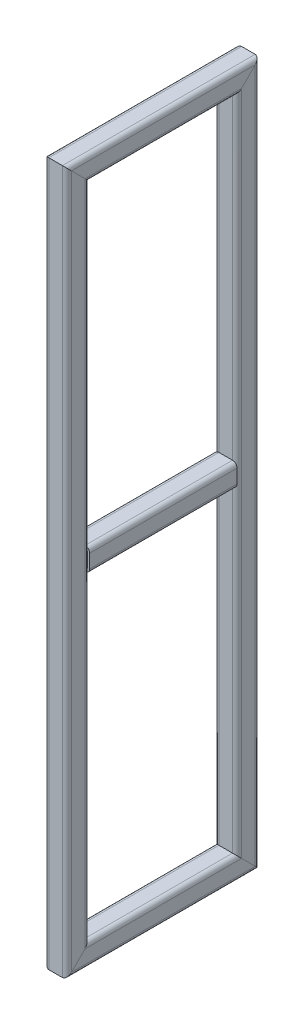
SolidWorks part; units mm, degrees
material "AISI 1020"
ref_plane "Alzado" through (0, 0, 0) normal (0, 0, 1) x (1, 0, 0)
ref_plane "Planta" through (0, 0, 0) normal (0, 1, 0) x (1, 0, 0)
ref_plane "Vista lateral" through (0, 0, 0) normal (1, 0, 0) x (0, 0, -1)
sketch "Croquis1" plane through (0, 0, 0) normal (1, 0, 0) x (0, 0, -1)
  line L0 (-75, 0) -> (75, 0)
  line L1 (-75, 300) -> (75, 300)
  line L2 (-75, 300) -> (-75, -300)
  line L3 (-75, -300) -> (75, -300)
  line L4 (75, 300) -> (75, -300)
  line L5 (-75, 300) -> (75, -300) construction
  line L6 (-75, -300) -> (75, 300) construction
  point P0 (0, 0)
  point P9 (0, 0)
  dimension "D1" = 600
  dimension "D2" = 150
other "Tubo cuadrado 20 X 20 X 2(1)"
ref_plane "Plano1" through (0, 300, 75) normal (0, -1, 0) x (0, 0, -1)
sketch "Sketch1" plane through (0, 300, 75) normal (0, -1, 0) x (0, 0, -1)
  line L0 (-6, -8) -> (6, -8)
  line L1 (-8, -6) -> (-8, 6)
  line L2 (6, 8) -> (-6, 8)
  line L3 (8, 6) -> (8, -6)
  line L4 (-6, -10) -> (6, -10)
  line L5 (-10, -6) -> (-10, 6)
  line L6 (6, 10) -> (-6, 10)
  line L7 (10, 6) -> (10, -6)
  arc A0 (10, 6) -> (6, 10) centre (6, 6) ccw
  arc A1 (6, -10) -> (10, -6) centre (6, -6) ccw
  arc A2 (-10, -6) -> (-6, -10) centre (-6, -6) ccw
  arc A3 (-6, 10) -> (-10, 6) centre (-6, 6) ccw
  arc A4 (-6, 8) -> (-8, 6) centre (-6, 6) ccw
  arc A5 (8, 6) -> (6, 8) centre (6, 6) ccw
  arc A6 (6, -8) -> (8, -6) centre (6, -6) ccw
  arc A7 (-8, -6) -> (-6, -8) centre (-6, -6) ccw
  point P0 (-10, 0)
  point P1 (10, 0)
  point P2 (0, 10)
  point P3 (0, -10)
  point P4 (0, 0)
  point P5 (-10, -10)
  point P6 (10, -10)
  point P7 (10, 10)
  point P8 (-10, 10)
  point P33 (0, 0)
  dimension "D1" = 4
  dimension "Thickness" = 2
  dimension "V_leg" = 20
